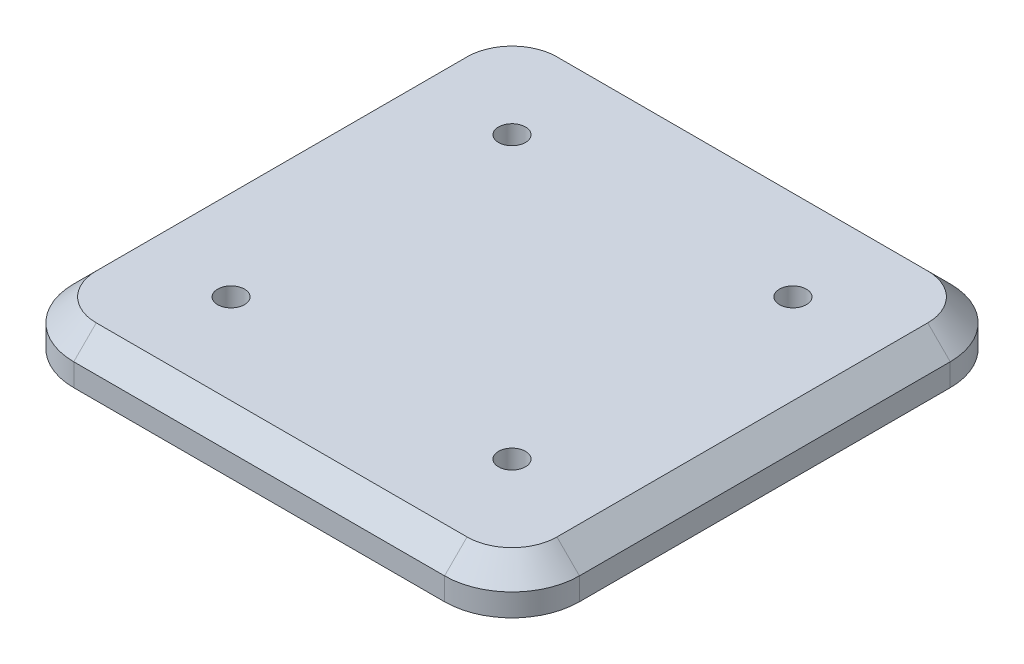
SolidWorks part; units mm, degrees
ref_plane "前基準面" through (0, 0, 0) normal (0, 0, 1) x (1, 0, 0)
ref_plane "上基準面" through (0, 0, 0) normal (0, 1, 0) x (1, 0, 0)
ref_plane "右基準面" through (0, 0, 0) normal (1, 0, 0) x (0, 0, -1)
sketch "草圖1" plane through (0, 0, 0) normal (0, 1, 0) x (1, 0, 0)
  line L1 (0, 0) -> (225, 0)
  line L2 (0, 0) -> (0, 225)
  line L3 (0, 225) -> (225, 225)
  line L4 (225, 0) -> (225, 225)
  dimension "D1" = 225
  dimension "D2" = 225
extrude "填料-伸長1" add sketch "草圖1" along normal blind 20
fillet "圓角1" radius 30 4 edges at (0, 10, -225) (225, 10, -225) (225, 10, 0) (0, 10, 0)
chamfer "導角1" distance 10 angle 45 8 edges at (0, 20, -112.5) (8.7868, 20, -8.7868) (8.7868, 20, -216.2132) (112.5, 20, 0) (112.5, 20, -225) (216.2132, 20, -8.7868) (216.2132, 20, -216.2132) (225, 20, -112.5)
sketch "草圖2" plane through (0, 0, 0) normal (0, -1, 0) x (1, 0, 0)
  line L0 (30, 0) -> (195, 0) construction
  line L1 (25, -25) -> (200, -25)
  line L2 (25, -25) -> (25, -200)
  line L3 (25, -200) -> (200, -200)
  line L4 (200, -25) -> (200, -200)
  line L5 (195, -225) -> (30, -225) construction
  line L6 (225, -30) -> (225, -195) construction
  line L7 (0, -195) -> (0, -30) construction
  dimension "D1" = 25
  dimension "D2" = 25
  dimension "D3" = 25
  dimension "D4" = 25
sketch "草圖4" plane through (0, 20, 0) normal (0, 1, 0) x (1, 0, 0)
  line L0 (25, 25) -> (25, 200) construction
  line L1 (50, 50) -> (175, 50)
  line L2 (50, 50) -> (50, 175)
  line L3 (50, 175) -> (175, 175)
  line L4 (175, 50) -> (175, 175)
  line L5 (25, 25) -> (200, 25) construction
  line L6 (200, 25) -> (200, 200) construction
  line L7 (25, 200) -> (200, 200) construction
  dimension "D1" = 25
  dimension "D2" = 25
  dimension "D3" = 25
  dimension "D4" = 25
hole_wizard "Ø20.0mm 定位孔1" positions "3D草圖2" profile "草圖6" hole size "Ø20.0" standard "ISO"
sketch3d "3D草圖2"
  point P0 (50, 20, -50)
  point P3 (50, 20, -175)
  point P6 (175, 20, -175)
  point P9 (175, 20, -50)
  point P12 (25, 0, -25)
  point P15 (200, 0, -25)
  point P18 (200, 0, -200)
  point P25 (25, 0, -200)
sketch "草圖6" plane through (50, 20, -50) normal (1, 0, 0) x (0, 0, 1)
  line L0 (0, 0) -> (0, 13.6052)
  line L1 (0, 13.6052) -> (6, 10)
  line L2 (6, 10) -> (6, 0)
  line L5 (6, 0) -> (0, 0)
  line L10 (0, 13.6052) -> (-6, 10) construction
  line L11 (0, -6.35) -> (0, 107.95) construction
  dimension "鑽孔直徑" = 12
  dimension "鑽孔深度" = 10
  dimension "導頭角度" = 118
